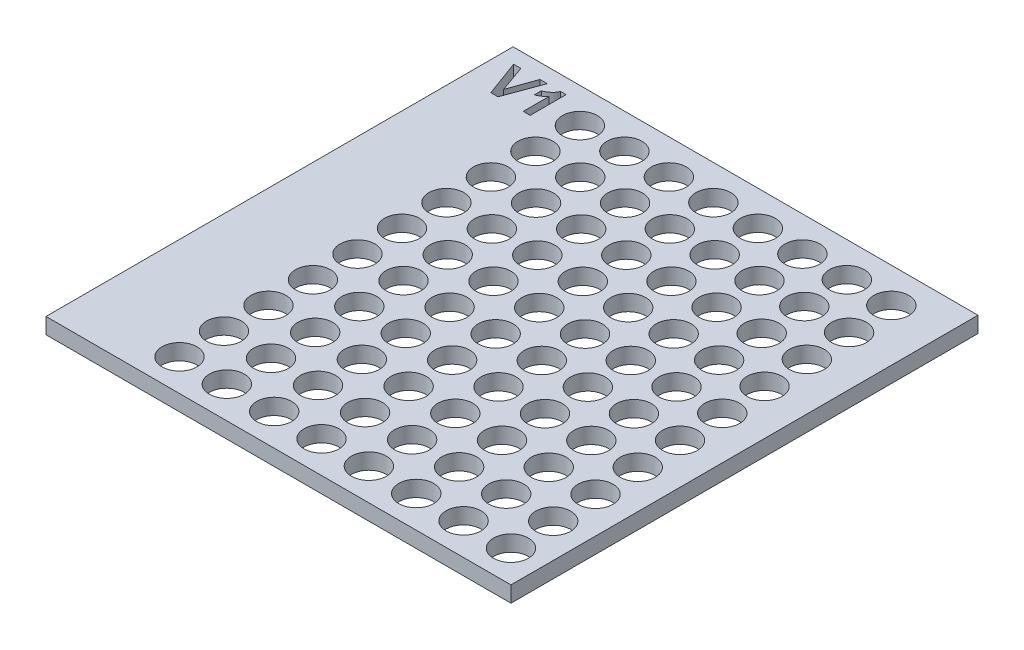
SolidWorks part; units mm, degrees
ref_plane "Front Plane" through (0, 0, 0) normal (0, 0, 1) x (1, 0, 0)
ref_plane "Top Plane" through (0, 0, 0) normal (0, 1, 0) x (1, 0, 0)
ref_plane "Right Plane" through (0, 0, 0) normal (1, 0, 0) x (0, 0, -1)
sketch "Sketch1" plane through (0, 0, 0) normal (0, 1, 0) x (1, 0, 0)
  line L0 (-46.4502, 36.5016) -> (-31.2102, 36.5016) construction
  line L1 (-46.4502, -46.6616) -> (46.4502, -46.6616)
  line L2 (-46.4502, -46.6616) -> (-46.4502, 46.6616)
  line L3 (-46.4502, 46.6616) -> (46.4502, 46.6616)
  line L4 (46.4502, -46.6616) -> (46.4502, 46.6616)
  line L5 (-46.4502, -46.6616) -> (46.4502, 46.6616) construction
  line L6 (-46.4502, 46.6616) -> (46.4502, -46.6616) construction
  line L7 (-26.1302, 39.6984) -> (46.4502, 39.6984) construction
  line L8 (-26.1302, 30.8084) -> (46.4502, 30.8084) construction
  line L9 (-26.1302, 21.9184) -> (46.4502, 21.9184) construction
  line L10 (-26.1302, 13.0284) -> (46.4502, 13.0284) construction
  line L11 (-26.1302, 4.1384) -> (46.4502, 4.1384) construction
  line L12 (-26.1302, -4.7516) -> (46.4502, -4.7516) construction
  line L13 (-26.1302, -13.6416) -> (46.4502, -13.6416) construction
  line L14 (-26.1302, -22.5316) -> (46.4502, -22.5316) construction
  line L15 (-26.1302, -31.4216) -> (46.4502, -31.4216) construction
  line L16 (-26.1302, -40.3116) -> (46.4502, -40.3116) construction
  circle A0 centre (-26.1302, 39.6984) radius 3.4925
  circle A1 centre (-26.1302, 30.8084) radius 3.4925
  circle A2 centre (-26.1302, 21.9184) radius 3.4925
  circle A3 centre (-26.1302, 13.0284) radius 3.4925
  circle A4 centre (-26.1302, 4.1384) radius 3.4925
  circle A5 centre (-26.1302, -4.7516) radius 3.4925
  circle A6 centre (-26.1302, -13.6416) radius 3.4925
  circle A7 centre (-26.1302, -22.5316) radius 3.4925
  circle A8 centre (-26.1302, -31.4216) radius 3.4925
  circle A9 centre (-26.1302, -40.3116) radius 3.4925
  circle A10 centre (-16.9862, 4.1384) radius 3.4925
  circle A11 centre (-7.8422, 4.1384) radius 3.4925
  circle A12 centre (1.3018, 4.1384) radius 3.4925
  circle A13 centre (10.4458, 4.1384) radius 3.4925
  circle A14 centre (19.5898, 4.1384) radius 3.4925
  circle A15 centre (28.7338, 4.1384) radius 3.4925
  circle A16 centre (37.8778, 4.1384) radius 3.4925
  circle A17 centre (-17.0497, 13.0284) radius 3.4925
  circle A18 centre (-7.9692, 13.0284) radius 3.4925
  circle A19 centre (1.1113, 13.0284) radius 3.4925
  circle A20 centre (10.1918, 13.0284) radius 3.4925
  circle A21 centre (19.2723, 13.0284) radius 3.4925
  circle A22 centre (28.3528, 13.0284) radius 3.4925
  circle A23 centre (37.4333, 13.0284) radius 3.4925
  circle A24 centre (-17.1132, 21.9184) radius 3.4925
  circle A25 centre (-8.0962, 21.9184) radius 3.4925
  circle A26 centre (0.9208, 21.9184) radius 3.4925
  circle A27 centre (9.9378, 21.9184) radius 3.4925
  circle A28 centre (18.9548, 21.9184) radius 3.4925
  circle A29 centre (27.9718, 21.9184) radius 3.4925
  circle A30 centre (36.9888, 21.9184) radius 3.4925
  circle A31 centre (-17.1767, 30.8084) radius 3.4925
  circle A32 centre (-8.2232, 30.8084) radius 3.4925
  circle A33 centre (0.7303, 30.8084) radius 3.4925
  circle A34 centre (9.6838, 30.8084) radius 3.4925
  circle A35 centre (18.6373, 30.8084) radius 3.4925
  circle A36 centre (27.5908, 30.8084) radius 3.4925
  circle A37 centre (36.5443, 30.8084) radius 3.4925
  circle A38 centre (-17.2402, 39.6984) radius 3.4925
  circle A39 centre (-8.3502, 39.6984) radius 3.4925
  circle A40 centre (0.5398, 39.6984) radius 3.4925
  circle A41 centre (9.4298, 39.6984) radius 3.4925
  circle A42 centre (18.3198, 39.6984) radius 3.4925
  circle A43 centre (27.2098, 39.6984) radius 3.4925
  circle A44 centre (36.0998, 39.6984) radius 3.4925
  circle A45 centre (-16.9227, -4.7516) radius 3.4925
  circle A46 centre (-7.7152, -4.7516) radius 3.4925
  circle A47 centre (1.4923, -4.7516) radius 3.4925
  circle A48 centre (10.6998, -4.7516) radius 3.4925
  circle A49 centre (19.9073, -4.7516) radius 3.4925
  circle A50 centre (29.1148, -4.7516) radius 3.4925
  circle A51 centre (38.3222, -4.7516) radius 3.4925
  circle A52 centre (-16.8592, -13.6416) radius 3.4925
  circle A53 centre (-7.5882, -13.6416) radius 3.4925
  circle A54 centre (1.6828, -13.6416) radius 3.4925
  circle A55 centre (10.9538, -13.6416) radius 3.4925
  circle A56 centre (20.2248, -13.6416) radius 3.4925
  circle A57 centre (29.4957, -13.6416) radius 3.4925
  circle A58 centre (38.7667, -13.6416) radius 3.4925
  circle A59 centre (-16.7957, -22.5316) radius 3.4925
  circle A60 centre (-7.4612, -22.5316) radius 3.4925
  circle A61 centre (1.8733, -22.5316) radius 3.4925
  circle A62 centre (11.2078, -22.5316) radius 3.4925
  circle A63 centre (20.5422, -22.5316) radius 3.4925
  circle A64 centre (29.8767, -22.5316) radius 3.4925
  circle A65 centre (39.2112, -22.5316) radius 3.4925
  circle A66 centre (-16.7322, -31.4216) radius 3.4925
  circle A67 centre (-7.3342, -31.4216) radius 3.4925
  circle A68 centre (2.0638, -31.4216) radius 3.4925
  circle A69 centre (11.4618, -31.4216) radius 3.4925
  circle A70 centre (20.8597, -31.4216) radius 3.4925
  circle A71 centre (30.2577, -31.4216) radius 3.4925
  circle A72 centre (39.6557, -31.4216) radius 3.4925
  circle A73 centre (-16.6687, -40.3116) radius 3.4925
  circle A74 centre (-7.2072, -40.3116) radius 3.4925
  circle A75 centre (2.2543, -40.3116) radius 3.4925
  circle A76 centre (11.7158, -40.3116) radius 3.4925
  circle A77 centre (21.1772, -40.3116) radius 3.4925
  circle A78 centre (30.6387, -40.3116) radius 3.4925
  circle A79 centre (40.1002, -40.3116) radius 3.4925
  text T0 "V1" font "Arial" height in points 28
  point P0 (0, 0)
  dimension "D4" = 6.985
  dimension "D1" = 10.16
  dimension "D2" = 15.24
  dimension "D11" = 9.144
  dimension "D17" = 9.0805
  dimension "D18" = 9.017
  dimension "D19" = 8.9535
  dimension "D20" = 8.89
  dimension "D21" = 9.2075
  dimension "D22" = 9.271
  dimension "D23" = 9.3345
  dimension "D24" = 9.398
  dimension "D25" = 9.4615
  dimension "D26" = 20.32
  dimension "D27" = 6.35
  dimension "D28" = 6.35
  dimension "D3" = 10
  dimension "D5" = 10
  dimension "D6" = 8
  dimension "D7" = 8
  dimension "D8" = 8
  dimension "D9" = 8
  dimension "D10" = 8
  dimension "D12" = 8
  dimension "D13" = 8
  dimension "D14" = 8
  dimension "D15" = 8
  dimension "D16" = 8
extrude "Boss-Extrude1" add sketch "Sketch1" along normal blind 3.175
